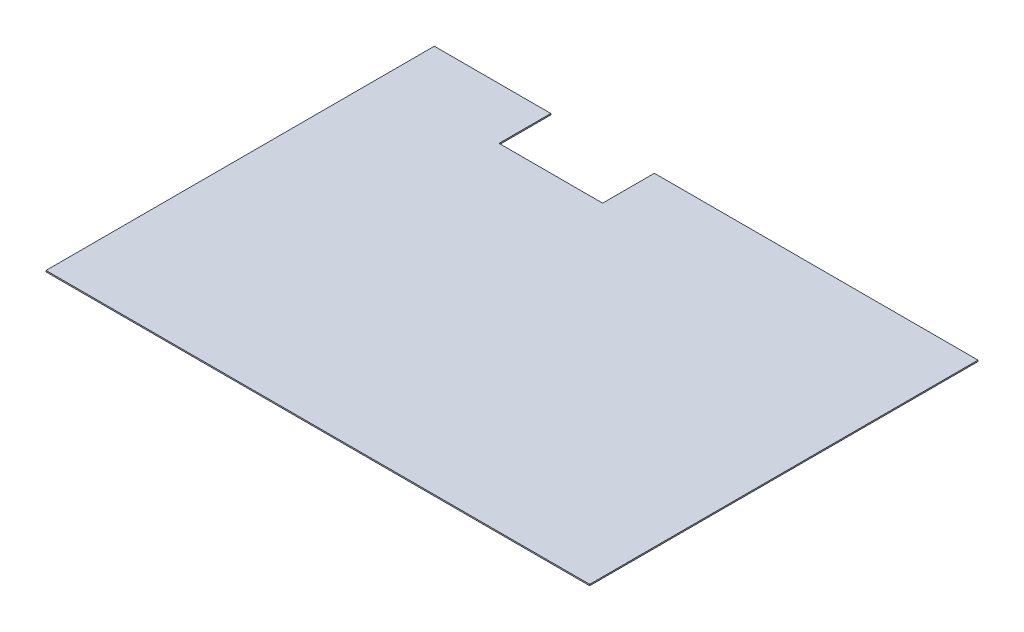
SolidWorks part; units mm, degrees
ref_plane "Front Plane" through (0, 0, 0) normal (0, 0, 1) x (1, 0, 0)
ref_plane "Top Plane" through (0, 0, 0) normal (0, 1, 0) x (1, 0, 0)
ref_plane "Right Plane" through (0, 0, 0) normal (1, 0, 0) x (0, 0, -1)
sketch "Sketch1" plane through (0, 0, 0) normal (0, 1, 0) x (1, 0, 0)
  line L1 (533.4, 381) -> (-533.4, 381)
  line L2 (533.4, 381) -> (533.4, -381)
  line L3 (533.4, -381) -> (-533.4, -381)
  line L4 (-533.4, 381) -> (-533.4, -381)
  line L5 (533.4, 381) -> (-533.4, -381) construction
  line L6 (533.4, -381) -> (-533.4, 381) construction
  point P0 (0, 0)
  dimension "D1" = 762
  dimension "D2" = 1066.8
extrude "Boss-Extrude1" add sketch "Sketch1" along normal blind 2.54 contours L1 L4 L3 L2
sketch "Sketch2" plane through (0, 2.54, 0) normal (0, 1, 0) x (1, 0, 0)
  line L0 (533.4, 381) -> (-533.4, 381) construction
  line L1 (-304.8, 381) -> (-101.6, 381)
  line L2 (-304.8, 381) -> (-304.8, 279.4)
  line L3 (-304.8, 279.4) -> (-101.6, 279.4)
  line L4 (-101.6, 381) -> (-101.6, 279.4)
  line L5 (-533.4, 381) -> (-533.4, -381) construction
  dimension "D1" = 101.6
  dimension "D2" = 203.2
  dimension "D3" = 228.6
extrude "Cut-Extrude1" cut sketch "Sketch2" against normal through all contours L3 L4 L1 L2
